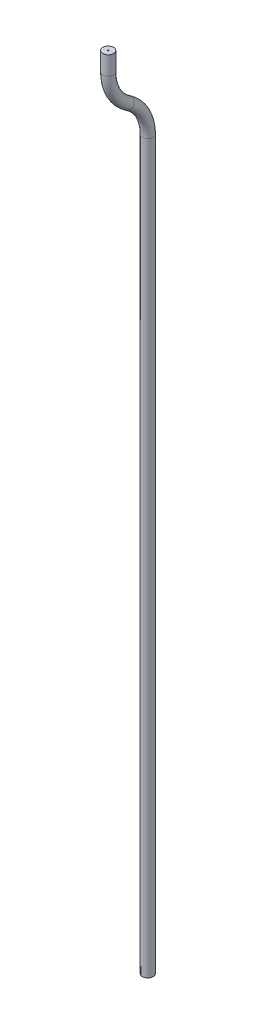
SolidWorks part; units mm, degrees
ref_plane "Front Plane" through (0, 0, 0) normal (0, 0, 1) x (1, 0, 0)
ref_plane "Top Plane" through (0, 0, 0) normal (0, 1, 0) x (1, 0, 0)
ref_plane "Right Plane" through (0, 0, 0) normal (1, 0, 0) x (0, 0, -1)
sketch "Illustrative smooth utility route" plane through (0, 0, 0) normal (1, 0, 0) x (0, 0, -1)
  line L0 (-17.35, 0) -> (-17.35, -6)
  line L1 (-4.5, -30) -> (-4.5, -266)
  arc A0 (-17.35, -6) -> (-10.925, -18) centre (-2.9313, -6) ccw
  arc A1 (-10.925, -18) -> (-4.5, -30) centre (-18.9187, -30) cw
sketch "Utility circular cross section" plane through (0, 0, 0) normal (0, 1, 0) x (1, 0, 0)
  circle A0 centre (0, -17.35) radius 1.75
  circle A1 centre (0, -17.35) radius 0.18
sweep "Native hollow utility sweep" add profiles "Utility circular cross section" path "Illustrative smooth utility route"
